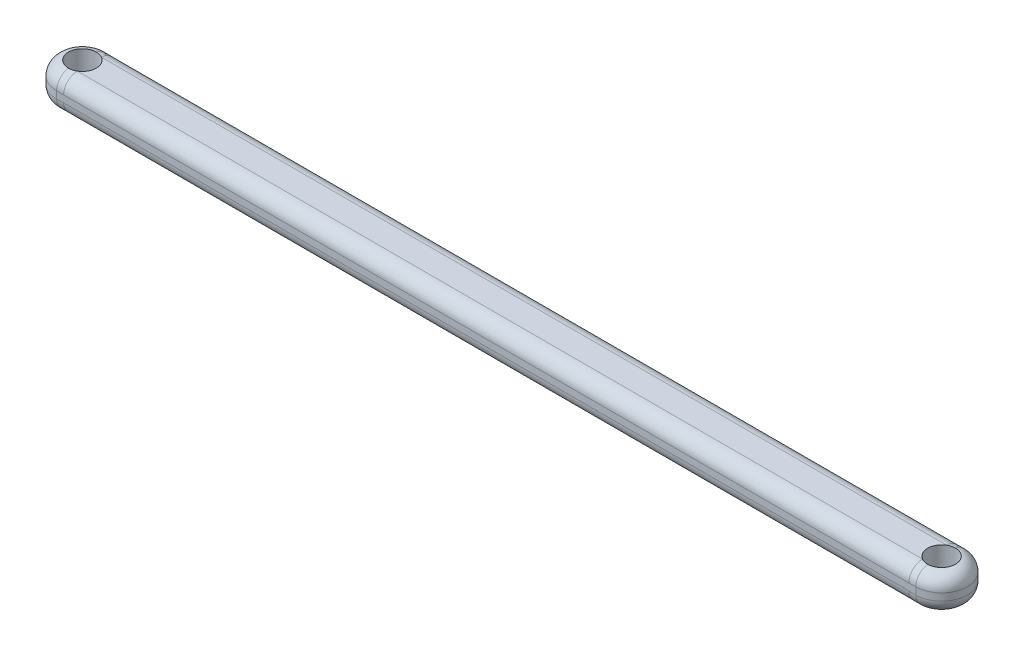
SolidWorks part; units mm, degrees
material "ABS PC"
ref_plane "Alzado" through (0, 0, 0) normal (1, 0, 0) x (0, 1, 0)
ref_plane "Planta" through (0, 0, 0) normal (0, 0, 1) x (0, 1, 0)
ref_plane "Vista lateral" through (0, 0, 0) normal (0, 1, 0) x (-1, 0, 0)
sketch "Croquis1" plane through (0, 0, 0) normal (0, 1, 0) x (-1, 0, 0)
  line L0 (0, 0) -> (250, 0) construction
  line L6 (0, -7.5) -> (250, -7.5)
  line L8 (250, 7.5) -> (0, 7.5)
  line L9 (125, -7.5) -> (125, 0) construction
  circle A0 centre (0, 0) radius 4.05
  circle A1 centre (250, 0) radius 4.05
  circle A2 centre (0, 0) radius 10 construction
  arc A3 (250, -7.5) -> (257.5, 0) centre (250, 0) ccw construction
  circle A8 centre (250, 0) radius 10 construction
  arc A9 (250, -7.5) -> (257.5, 0) centre (250, 0) ccw construction
  arc A10 (250, -7.5) -> (250, 7.5) centre (250, 0) ccw
  arc A12 (0, -7.5) -> (0, 7.5) centre (0, 0) cw
  point P8 (0, 0)
  dimension "D3" = 8.1
  dimension "D4" = 20
  dimension "D1" = 250
  dimension "D2" = 15
extrude "Saliente-Extruir1" add sketch "Croquis1" along normal mid plane 10
fillet "Redondeo6" radius 4 4 edges at (-125, 5, 7.5) (-125, -5, 7.5) (-125, 5, -7.5) (-125, -5, -7.5)
sketch "Croquis2" plane through (0, -5, 0) normal (0, 1, 0) x (-1, 0, 0)
  circle A0 centre (0, 0) radius 6.2
  circle A1 centre (250, 0) radius 6.2
  dimension "D1" = 12.4
extrude "Cortar-Extruir1" [suppressed] cut sketch "Croquis2" along normal blind 1.2
equation "\"L1\"= 250"
equation "\"ancho\"= 15"
equation "\"esp\"= 10"
equation "\"agujeros\"=8.1"
equation "\"D1@Croquis1\"=\"L1\""
equation "\"D2@Croquis1\"=\"ancho\""
equation "\"D3@Croquis1\"=\"agujeros\""
equation "\"D1@Saliente-Extruir1\"=\"esp\""
